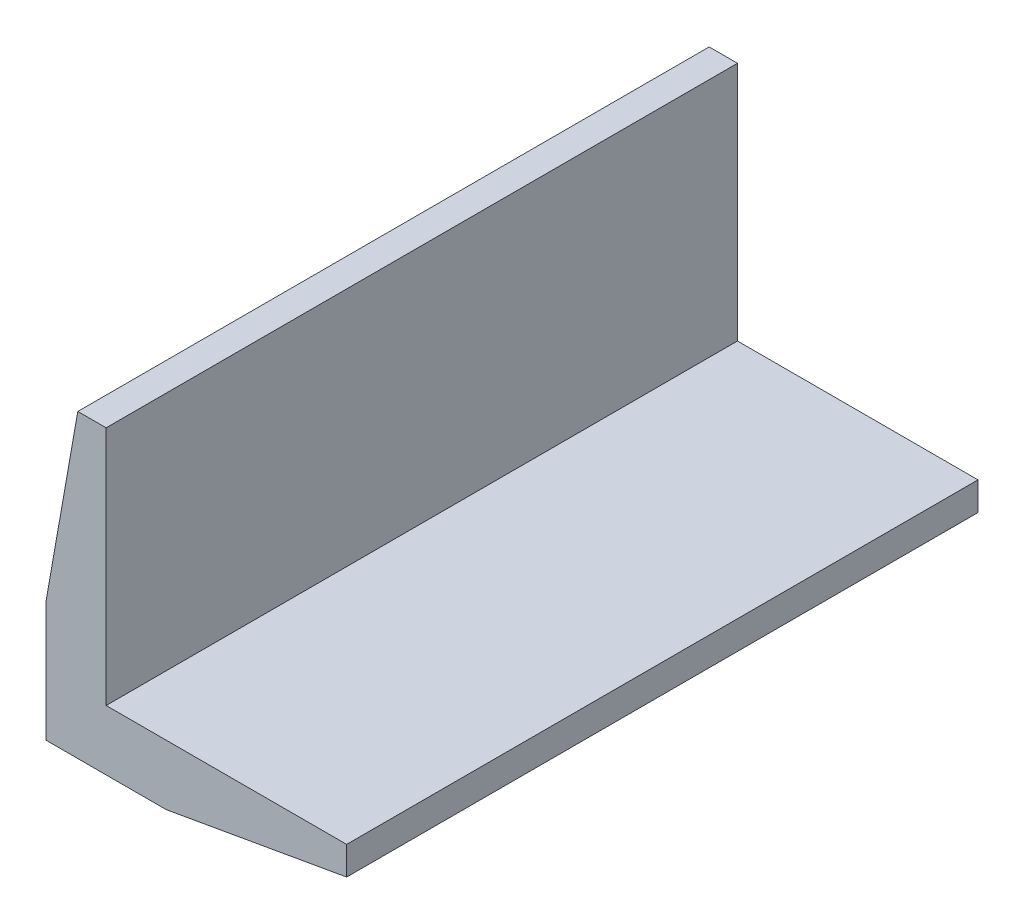
SolidWorks part; units mm, degrees
ref_plane "Front Plane" through (0, 0, 0) normal (0, 0, 1) x (1, 0, 0)
ref_plane "Top Plane" through (0, 0, 0) normal (0, 1, 0) x (1, 0, 0)
ref_plane "Right Plane" through (0, 0, 0) normal (1, 0, 0) x (0, 0, -1)
sketch "Sketch1" plane through (0, 0, 0) normal (0, 0, 1) x (1, 0, 0)
  line L0 (0, 0) -> (0, 20)
  line L1 (0, 20) -> (4, 20)
  line L2 (4, 20) -> (4, 4)
  line L3 (4, 4) -> (20, 4)
  line L4 (20, 4) -> (20, 0)
  line L5 (20, 0) -> (0, 0)
  point P3 (22.5409, 4)
  dimension "D1" = 4
  dimension "D2" = 20
extrude "Boss-Extrude1" add sketch "Sketch1" along normal blind 42
ref_plane "Plane1" through (0, 0, 0) normal (0.7071, -0.7071, 0) x (0, 0, -1)
sketch "Sketch2" plane through (0, 0, 0) normal (0.7071, -0.7071, 0) x (0, 0, -1)
  line L0 (-42, 0) -> (-42, 5.6569) construction
  line L1 (-42, 2.8284) -> (0, 2.8284) construction
  line L2 (0, 2.8284) -> (0, 0) construction
  line L3 (0, 0) -> (0, 14.1421) construction
  circle A0 centre (-40, 2.8284) radius 1.125
  circle A1 centre (-37.2857, 2.8284) radius 1.125
  circle A2 centre (-34.5714, 2.8284) radius 1.125
  circle A3 centre (-31.8571, 2.8284) radius 1.125
  circle A4 centre (-29.1429, 2.8284) radius 1.125
  circle A5 centre (-26.4286, 2.8284) radius 1.125
  circle A6 centre (-23.7143, 2.8284) radius 1.125
  circle A7 centre (-21, 2.8284) radius 1.125
  circle A8 centre (-18.2857, 2.8284) radius 1.125
  circle A9 centre (-15.5714, 2.8284) radius 1.125
  circle A10 centre (-12.8571, 2.8284) radius 1.125
  circle A11 centre (-10.1429, 2.8284) radius 1.125
  circle A12 centre (-7.4286, 2.8284) radius 1.125
  circle A13 centre (-4.7143, 2.8284) radius 1.125
  circle A14 centre (-2, 2.8284) radius 1.125
  dimension "D1" = 2
  dimension "D3" = 2.25
  dimension "D4" = 2
  dimension "D2" = 15
extrude "Cut-Extrude1" cut sketch "Sketch2" against normal through all both and the other way through all
chamfer "Chamfer1" distance 12 angle 10 1 edges at (20, 0, 21)
chamfer "Chamfer2" distance 12 angle 10 1 edges at (0, 20, 21)
